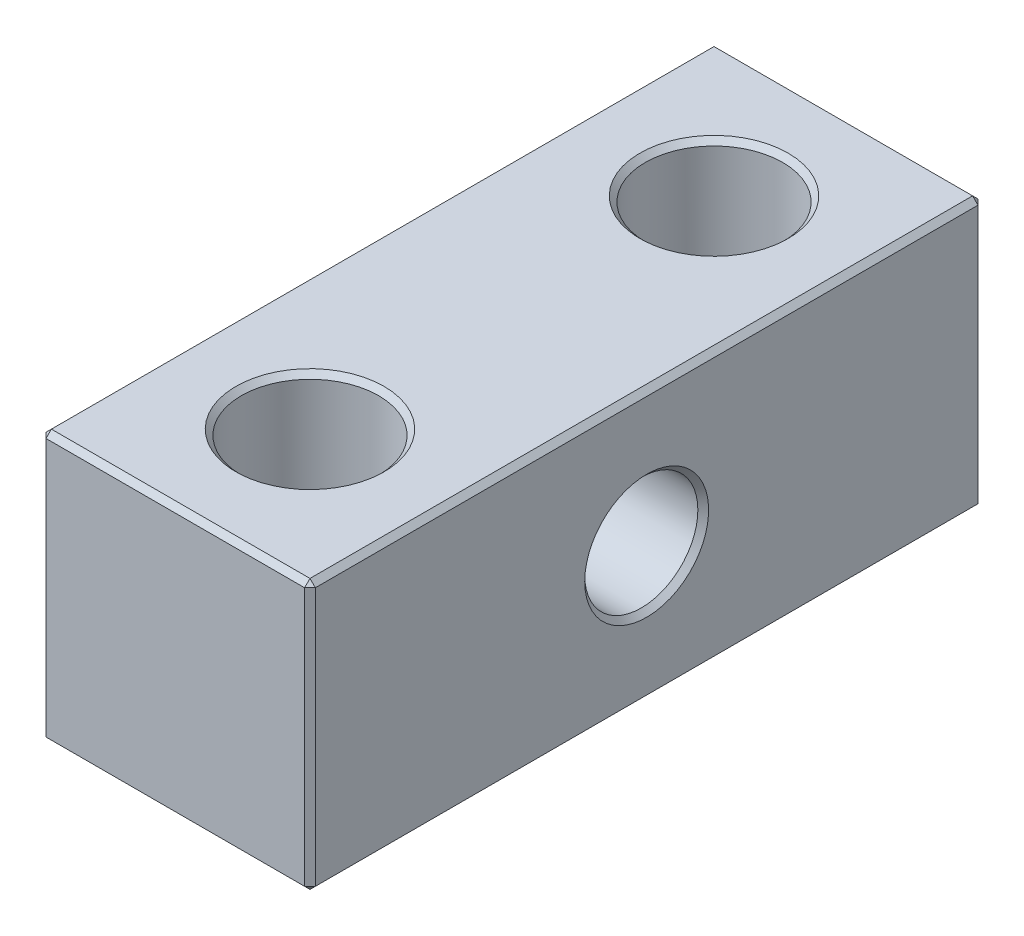
SolidWorks part; units mm, degrees
ref_plane "前视基准面" through (0, 0, 0) normal (0, 0, 1) x (1, 0, 0)
ref_plane "上视基准面" through (0, 0, 0) normal (0, 1, 0) x (1, 0, 0)
ref_plane "右视基准面" through (0, 0, 0) normal (1, 0, 0) x (0, 0, -1)
sketch "草图1" plane through (0, 0, 0) normal (0, 0, 1) x (1, 0, 0)
  line L1 (-5, 5) -> (5, 5)
  line L2 (-5, 5) -> (-5, -5)
  line L3 (-5, -5) -> (5, -5)
  line L4 (5, 5) -> (5, -5)
  line L5 (-5, 5) -> (5, -5) construction
  line L6 (-5, -5) -> (5, 5) construction
  point P0 (0, 0)
  dimension "D1" = 10
extrude "凸台-拉伸1" add sketch "草图1" along normal mid plane 25
hole_wizard "M5 螺纹孔1" positions "草图2" profile "草图3" tap size "M5" standard "GB" end condition through all
sketch "草图2" plane through (5, 0, 0) normal (1, 0, 0) x (0, 0, -1)
  line L0 (0, 0) -> (50000, 0) construction
  line L1 (12.5, -5) -> (12.5, 5) construction
  point P0 (0, 0)
  dimension "D1" = 12.5
sketch "草图3" plane through (5, 0, 0) normal (0, 1, 0) x (0, 0, -1)
  line L0 (0, 0) -> (0, 10)
  line L1 (0, 10) -> (2.1, 10)
  line L2 (2.1, 10) -> (2.1, 0)
  line L5 (2.1, 0) -> (0, 0)
  line L11 (0, -6.35) -> (0, 107.95) construction
  dimension "通孔螺纹孔钻头直径" = 4.2
  dimension "通孔螺纹孔钻头深度" = 10
cosmetic thread "孔螺蚊线3"
hole_wizard "Ø5.1 (5.1) 直径孔1" positions "草图6" profile "草图7" hole size "Ø5.1" standard "GB" end condition through all
sketch "草图6" plane through (0, 5, 0) normal (0, 1, 0) x (1, 0, 0)
  line L0 (0, 0) -> (0, 50000) construction
  line L1 (0, 0) -> (50000, 0) construction
  point P0 (0, -7.5)
  point P2 (0, 7.5)
  dimension "D1" = 15
sketch "草图7" plane through (0, 5, 7.5) normal (1, 0, 0) x (0, 0, 1)
  line L0 (0, 0) -> (0, 10)
  line L1 (0, 10) -> (2.55, 10)
  line L2 (2.55, 10) -> (2.55, 0)
  line L5 (2.55, 0) -> (0, 0)
  line L11 (0, -6.35) -> (0, 107.95) construction
  dimension "通孔孔直径" = 5.1
  dimension "通孔孔深度" = 10
chamfer "倒角1" distance 0.2 angle 45 18 edges at (-5, 0, -2.1) (0, -5, 12.5) (0, -5, -12.5) (-5, -5, 0) (-5, 0, -12.5) (0, 5, 12.5) (-5, 5, 0) (0, 5, -12.5) (5, -5, 0) (5, 5, 0) (5, 0, -12.5) (5, 0, -2.1) (-5, 0, 12.5) (5, 0, 12.5) (0, -5, -4.95) (0, -5, 10.05) (0, 5, -4.95) (0, 5, 10.05)
